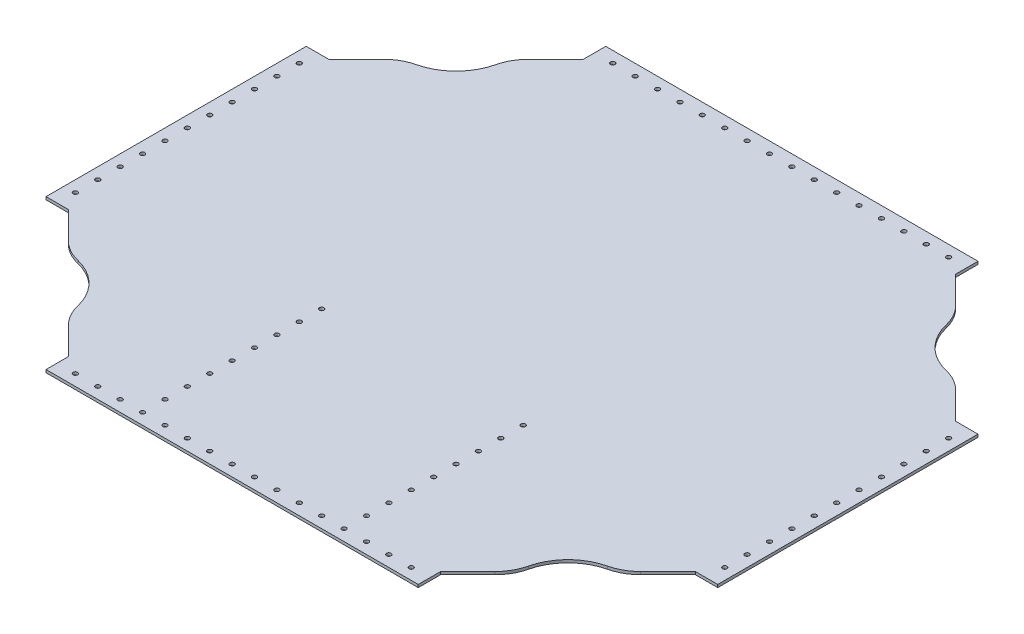
SolidWorks part; units mm, degrees
material "6061-T6 (SS)"
ref_plane "Front Plane" through (0, 0, 0) normal (0, 0, 1) x (1, 0, 0)
ref_plane "Top Plane" through (0, 0, 0) normal (0, 1, 0) x (1, 0, 0)
ref_plane "Right Plane" through (0, 0, 0) normal (1, 0, 0) x (0, 0, -1)
sketch "Sketch2" plane through (0, 0, 0) normal (0, 1, 0) x (1, 0, 0)
  line L0 (-381, 0) -> (381, 0) construction
  line L1 (0, -317.5) -> (0, 317.5) construction
  line L2 (-381, -147.6375) -> (-381, 147.6375)
  line L3 (211.1375, 317.5) -> (-211.1375, 317.5)
  line L4 (381, -147.6375) -> (381, 147.6375)
  line L5 (-211.1375, -317.5) -> (211.1375, -317.5) construction
  line L10 (-175.2165, 292.1) -> (175.2165, 292.1) construction
  line L11 (-355.6, -111.7165) -> (-355.6, 111.7165) construction
  line L12 (-175.2165, -292.1) -> (175.2165, -292.1) construction
  line L13 (355.6, -111.7165) -> (355.6, 111.7165) construction
  line L14 (-355.6, -111.7165) -> (-175.2165, -292.1) construction
  line L15 (175.2165, -292.1) -> (355.6, -111.7165) construction
  line L16 (175.2165, 292.1) -> (355.6, 111.7165) construction
  line L17 (-355.6, 111.7165) -> (-175.2165, 292.1) construction
  line L18 (-114.3, -304.8) -> (-88.9, -304.8) construction
  line L19 (211.1375, 292.1) -> (242.1157, 261.1218)
  line L21 (355.6, -88.9) -> (152.4, -88.9) construction
  line L22 (-355.6, -63.5) -> (-355.6, 111.7165) construction
  line L24 (-175.2165, 292.1) -> (175.2165, 292.1) construction
  line L26 (355.6, 111.7165) -> (355.6, -63.5) construction
  line L27 (355.6, -88.9) -> (355.6, -111.7165) construction
  line L29 (175.2165, -292.1) -> (152.4, -292.1) construction
  line L31 (-355.6, -111.7165) -> (-355.6, -88.9) construction
  line L35 (-127, -292.1) -> (-175.2165, -292.1) construction
  line L36 (-211.1375, -317.5) -> (-101.6, -317.5)
  line L37 (211.1375, -317.5) -> (-101.6, -317.5)
  line L38 (-127, -292.1) -> (-127, -88.9) construction
  line L41 (152.4, -292.1) -> (152.4, -88.9) construction
  line L43 (-127, -88.9) -> (-355.6, -88.9) construction
  line L44 (-114.3, -279.4) -> (-114.3, -254) construction
  line L45 (175.2165, 292.1) -> (224.1552, 243.1613) construction
  line L46 (-368.3, -76.2) -> (-368.3, -101.6) construction
  line L50 (381, 147.6375) -> (355.6, 147.6375)
  line L51 (355.6, 209.55) -> (355.6, -209.55) construction
  line L52 (371.475, 147.6375) -> (365.125, 147.6375) construction
  line L53 (355.6, 147.6375) -> (324.6218, 178.6157)
  line L54 (211.1375, 317.5) -> (211.1375, 292.1)
  line L56 (-273.05, 292.1) -> (273.05, 292.1) construction
  line L57 (211.1375, 301.625) -> (211.1375, 307.975) construction
  line L58 (242.1157, 261.1218) -> (224.1552, 243.1613) construction
  line L59 (255.6257, 236.9147) -> (237.6652, 218.9542) construction
  line L60 (282.4542, 174.1652) -> (300.4147, 192.1257) construction
  line L61 (306.6613, 160.6552) -> (355.6, 111.7165) construction
  line L62 (-175.2165, 292.1) -> (-224.1552, 243.1613) construction
  line L63 (-306.6613, 160.6552) -> (-355.6, 111.7165) construction
  line L64 (-381, 147.6375) -> (-355.6, 147.6375)
  line L65 (-355.6, 147.6375) -> (-324.6218, 178.6157)
  line L66 (-211.1375, 292.1) -> (-242.1157, 261.1218)
  line L67 (-211.1375, 317.5) -> (-211.1375, 292.1)
  line L68 (175.2165, -292.1) -> (224.1552, -243.1613) construction
  line L69 (306.6613, -160.6552) -> (355.6, -111.7165) construction
  line L70 (-381, -147.6375) -> (-355.6, -147.6375)
  line L71 (-355.6, -147.6375) -> (-324.6218, -178.6157)
  line L72 (-306.6613, -160.6552) -> (-355.6, -111.7165) construction
  line L73 (-175.2165, -292.1) -> (-224.1552, -243.1613) construction
  line L74 (-211.1375, -292.1) -> (-242.1157, -261.1218)
  line L75 (-211.1375, -317.5) -> (-211.1375, -292.1)
  line L76 (381, -147.6375) -> (355.6, -147.6375)
  line L77 (355.6, -147.6375) -> (324.6218, -178.6157)
  line L78 (211.1375, -317.5) -> (211.1375, -292.1)
  line L79 (211.1375, -292.1) -> (242.1157, -261.1218)
  circle A0 centre (-190.5, 304.8) radius 2.5527
  circle A1 centre (-165.1, 304.8) radius 2.5527
  circle A2 centre (-139.7, 304.8) radius 2.5527
  circle A3 centre (-114.3, 304.8) radius 2.5527
  circle A4 centre (-88.9, 304.8) radius 2.5527
  circle A5 centre (-63.5, 304.8) radius 2.5527
  circle A6 centre (-38.1, 304.8) radius 2.5527
  circle A7 centre (-12.7, 304.8) radius 2.5527
  circle A8 centre (12.7, 304.8) radius 2.5527
  circle A9 centre (38.1, 304.8) radius 2.5527
  circle A10 centre (63.5, 304.8) radius 2.5527
  circle A11 centre (88.9, 304.8) radius 2.5527
  circle A12 centre (114.3, 304.8) radius 2.5527
  circle A13 centre (139.7, 304.8) radius 2.5527
  circle A14 centre (368.3, 127) radius 2.5527
  circle A15 centre (368.3, 101.6) radius 2.5527
  circle A16 centre (368.3, 76.2) radius 2.5527
  circle A17 centre (368.3, 50.8) radius 2.5527
  circle A18 centre (368.3, 25.4) radius 2.5527
  circle A19 centre (368.3, 0) radius 2.5527
  circle A20 centre (368.3, -25.4) radius 2.5527
  circle A21 centre (368.3, -50.8) radius 2.5527
  circle A22 centre (368.3, -76.2) radius 2.5527
  circle A23 centre (139.7, -304.8) radius 2.5527
  circle A24 centre (114.3, -304.8) radius 2.5527
  circle A33 centre (-114.3, -304.8) radius 2.5527
  circle A34 centre (-139.7, -304.8) radius 2.5527
  circle A35 centre (-165.1, -304.8) radius 2.5527
  circle A36 centre (-190.5, -304.8) radius 2.5527
  circle A37 centre (-368.3, -76.2) radius 2.5527
  circle A38 centre (-368.3, -50.8) radius 2.5527
  circle A39 centre (-368.3, -25.4) radius 2.5527
  circle A40 centre (-368.3, 0) radius 2.5527
  circle A41 centre (-368.3, 25.4) radius 2.5527
  circle A42 centre (-368.3, 50.8) radius 2.5527
  circle A43 centre (-368.3, 76.2) radius 2.5527
  circle A44 centre (-368.3, 101.6) radius 2.5527
  circle A45 centre (-368.3, 127) radius 2.5527
  circle A90 centre (-114.3, -279.4) radius 2.5527
  circle A91 centre (-114.3, -254) radius 2.5527
  circle A92 centre (-114.3, -228.6) radius 2.5527
  circle A93 centre (-114.3, -203.2) radius 2.5527
  circle A94 centre (-114.3, -177.8) radius 2.5527
  circle A95 centre (-114.3, -152.4) radius 2.5527
  circle A96 centre (-114.3, -127) radius 2.5527
  circle A97 centre (-114.3, -101.6) radius 2.5527
  circle A98 centre (114.3, -279.4) radius 2.5527
  circle A99 centre (114.3, -254) radius 2.5527
  circle A100 centre (114.3, -228.6) radius 2.5527
  circle A101 centre (114.3, -203.2) radius 2.5527
  circle A102 centre (114.3, -177.8) radius 2.5527
  circle A103 centre (114.3, -152.4) radius 2.5527
  circle A104 centre (114.3, -127) radius 2.5527
  circle A105 centre (114.3, -101.6) radius 2.5527
  circle A106 centre (165.1, 304.8) radius 2.5527
  circle A107 centre (190.5, 304.8) radius 2.5527
  circle A108 centre (368.3, -101.6) radius 2.5527
  circle A109 centre (368.3, -127) radius 2.5527
  circle A110 centre (165.1, -304.8) radius 2.5527
  circle A111 centre (190.5, -304.8) radius 2.5527
  circle A113 centre (-368.3, -101.6) radius 2.5527
  circle A114 centre (-368.3, -127) radius 2.5527
  arc A143 (255.6257, 236.9147) -> (300.4147, 192.1257) centre (314.325, 250.825) ccw
  arc A144 (324.6218, 178.6157) -> (300.4147, 192.1257) centre (288.7008, 142.6947) ccw
  arc A145 (242.1157, 261.1218) -> (255.6257, 236.9147) centre (206.1947, 225.2008) cw
  arc A146 (224.1552, 243.1613) -> (237.6652, 218.9542) centre (188.2342, 207.2402) cw construction
  arc A147 (237.6652, 218.9542) -> (282.4542, 174.1652) centre (296.3645, 232.8645) ccw construction
  arc A148 (282.4542, 174.1652) -> (306.6613, 160.6552) centre (270.7402, 124.7342) cw construction
  arc A149 (-224.1552, 243.1613) -> (-237.6652, 218.9542) centre (-188.2342, 207.2402) ccw construction
  arc A150 (-237.6652, 218.9542) -> (-282.4542, 174.1652) centre (-296.3645, 232.8645) cw construction
  arc A151 (-282.4542, 174.1652) -> (-306.6613, 160.6552) centre (-270.7402, 124.7342) ccw construction
  arc A152 (-324.6218, 178.6157) -> (-300.4147, 192.1257) centre (-288.7008, 142.6947) cw
  arc A153 (-255.6257, 236.9147) -> (-300.4147, 192.1257) centre (-314.325, 250.825) cw
  arc A154 (-242.1157, 261.1218) -> (-255.6257, 236.9147) centre (-206.1947, 225.2008) ccw
  arc A155 (224.1552, -243.1613) -> (237.6652, -218.9542) centre (188.2342, -207.2402) ccw construction
  arc A156 (237.6652, -218.9542) -> (282.4542, -174.1652) centre (296.3645, -232.8645) cw construction
  arc A157 (282.4542, -174.1652) -> (306.6613, -160.6552) centre (270.7402, -124.7342) ccw construction
  arc A158 (-224.1552, -243.1613) -> (-237.6652, -218.9542) centre (-188.2342, -207.2402) cw construction
  arc A159 (-237.6652, -218.9542) -> (-282.4542, -174.1652) centre (-296.3645, -232.8645) ccw construction
  arc A160 (-324.6218, -178.6157) -> (-300.4147, -192.1257) centre (-288.7008, -142.6947) ccw
  arc A161 (-282.4542, -174.1652) -> (-306.6613, -160.6552) centre (-270.7402, -124.7342) cw construction
  arc A162 (-255.6257, -236.9147) -> (-300.4147, -192.1257) centre (-314.325, -250.825) ccw
  arc A163 (-242.1157, -261.1218) -> (-255.6257, -236.9147) centre (-206.1947, -225.2008) cw
  arc A164 (324.6218, -178.6157) -> (300.4147, -192.1257) centre (288.7008, -142.6947) cw
  arc A165 (255.6257, -236.9147) -> (300.4147, -192.1257) centre (314.325, -250.825) cw
  arc A166 (242.1157, -261.1218) -> (255.6257, -236.9147) centre (206.1947, -225.2008) ccw
  circle A167 centre (-88.9, -304.8) radius 2.5527
  circle A168 centre (-63.5, -304.8) radius 2.5527
  circle A169 centre (-38.1, -304.8) radius 2.5527
  circle A170 centre (-12.7, -304.8) radius 2.5527
  circle A171 centre (12.7, -304.8) radius 2.5527
  circle A172 centre (38.1, -304.8) radius 2.5527
  circle A173 centre (63.5, -304.8) radius 2.5527
  circle A174 centre (88.9, -304.8) radius 2.5527
  point P4 (0, 0)
  point P8 (0, 0)
  point P11 (-381, 0)
  point P14 (0, 317.5)
  point P17 (381, 0)
  point P20 (0, -317.5)
  point P23 (0, 292.1)
  point P26 (-355.6, 0)
  point P29 (0, -292.1)
  point P32 (355.6, 0)
  dimension "D8" = 12.7
  dimension "D9" = 5.1054
  dimension "D10" = 190.5
  dimension "D12" = 12.7
  dimension "D13" = 5.1054
  dimension "D26" = 12.7
  dimension "D31" = 25.4
  dimension "D32" = 25.4
  dimension "D7" = 120.65
  dimension "D21" = 50.8
  dimension "D5" = 228.6
  dimension "D4" = 254
  dimension "D20" = 5.1054
  dimension "D22" = 5.1054
  dimension "D25" = 12.7
  dimension "D1" = 635
  dimension "D2" = 762
  dimension "D3" = 25.4
  dimension "D6" = 25.4
  dimension "D14" = 127
  dimension "D15" = 11
  dimension "D16" = 25.4
  dimension "D17" = 25.4
  dimension "D18" = 228.6
  dimension "D19" = 12.7
  dimension "D23" = 9
  dimension "D24" = 25.4
  dimension "D29" = 25.4
  dimension "D35" = 25.4
  dimension "D11" = 16
  dimension "D28" = 8
  dimension "D30" = 3
  dimension "D34" = 3
extrude "Boss-Extrude1" add sketch "Sketch2" along normal blind 3.175 contours L11 L17 L10 L16 L13 L15 L12 L14
